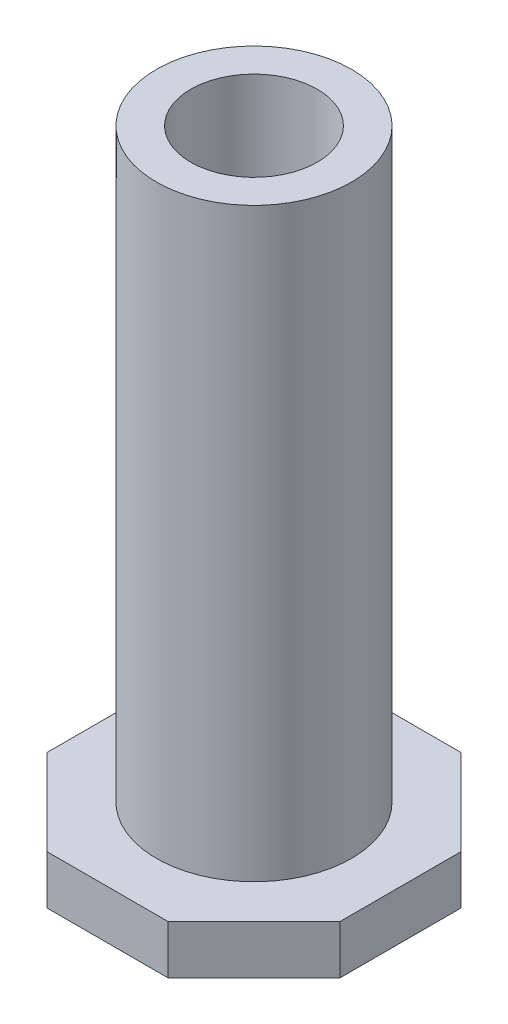
SolidWorks part; units mm, degrees
material "ABS"
ref_plane "Front Plane" through (0, 0, 0) normal (0, 0, 1) x (1, 0, 0)
ref_plane "Top Plane" through (0, 0, 0) normal (0, 1, 0) x (1, 0, 0)
ref_plane "Right Plane" through (0, 0, 0) normal (1, 0, 0) x (0, 0, -1)
sketch "Sketch1" plane through (0, 0, 0) normal (0, 1, 0) x (1, 0, 0)
  line L1 (4.7625, -1.9727) -> (4.7625, 1.9727)
  line L2 (4.7625, 1.9727) -> (1.9727, 4.7625)
  line L3 (1.9727, 4.7625) -> (-1.9727, 4.7625)
  line L4 (-1.9727, 4.7625) -> (-4.7625, 1.9727)
  line L5 (-4.7625, 1.9727) -> (-4.7625, -1.9727)
  line L6 (-4.7625, -1.9727) -> (-1.9727, -4.7625)
  line L7 (-1.9727, -4.7625) -> (1.9727, -4.7625)
  line L8 (1.9727, -4.7625) -> (4.7625, -1.9727)
  circle A0 centre (0, 0) radius 4.7625 construction
  dimension "D1" = 9.525
extrude "Boss-Extrude1" add sketch "Sketch1" along normal blind 1.5875
sketch "Sketch2" plane through (0, 1.5875, 0) normal (0, 1, 0) x (1, 0, 0)
  circle A0 centre (0, 0) radius 3.175
  dimension "D1" = 6.35
extrude "Boss-Extrude2" add sketch "Sketch2" along normal blind 19.05
sketch "Sketch3" plane through (0, 20.6375, 0) normal (0, 1, 0) x (1, 0, 0)
  circle A0 centre (0, 0) radius 2.0574
  dimension "D1" = 4.1148
extrude "Cut-Extrude1" cut sketch "Sketch3" against normal blind 6.35
